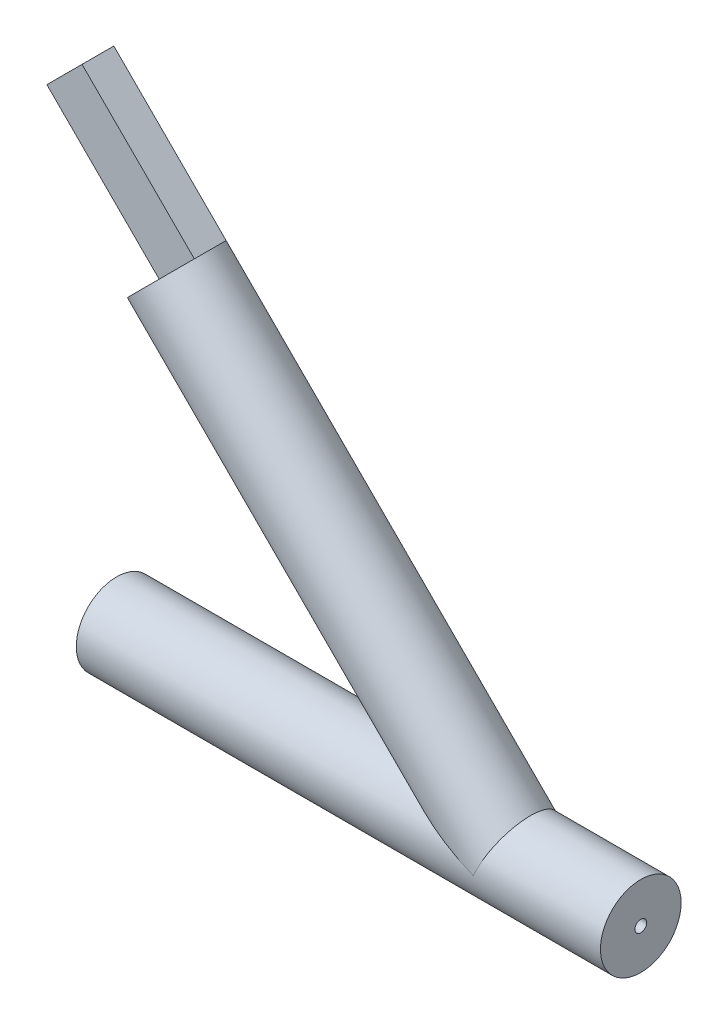
SolidWorks part; units mm, degrees
ref_plane "Front Plane" through (0, 0, 0) normal (0, 0, 1) x (1, 0, 0)
ref_plane "Top Plane" through (0, 0, 0) normal (0, 1, 0) x (1, 0, 0)
ref_plane "Right Plane" through (0, 0, 0) normal (1, 0, 0) x (0, 0, -1)
sketch "Sketch1" plane through (0, 0, 0) normal (1, 0, 0) x (0, 0, -1)
  circle A0 centre (0, 0) radius 12.7
  dimension "D1" = 25.4
extrude "Boss-Extrude1" add sketch "Sketch1" along normal blind 165 contours A0
sketch "Sketch4" plane through (0, 0, 0) normal (0, 1, 0) x (1, 0, 0)
  line L0 (125, -73.5137) -> (125, 26.4863)
  line L1 (165, -12.7) -> (165, 12.7) construction
  dimension "D1" = 40
ref_plane "Plane1" through (62.5, -62.5, 0) normal (-0.7071, 0.7071, 0) x (0.7071, 0.7071, 0)
sketch "Sketch6" plane through (0, 0, 0) normal (0, 1, 0) x (1, 0, 0)
  line L1 (165, -12.7) -> (165, 12.7) construction
  circle A0 centre (125, 0) radius 20
  dimension "D1" = 40
  dimension "D2" = 0
sketch "Sketch7" plane through (62.5, -62.5, 0) normal (-0.7071, 0.7071, 0) x (0.7071, 0.7071, 0)
  circle A0 centre (88.3883, 0) radius 12.7
  dimension "D1" = 25.4
extrude "Boss-Extrude3" add sketch "Sketch7" along normal blind 150 contours A0
sketch "Sketch10" plane through (-43.566, 43.566, 0) normal (-0.7071, 0.7071, 0) x (0, 0, 1)
  line L1 (-10, 96.2171) -> (10, 96.2171)
  line L2 (-10, 96.2171) -> (-10, 80.5596)
  line L3 (-10, 80.5596) -> (10, 80.5596)
  line L4 (10, 96.2171) -> (10, 80.5596)
  line L5 (-10, 96.2171) -> (10, 80.5596) construction
  line L6 (-10, 80.5596) -> (10, 96.2171) construction
  line L7 (-10, 96.2171) -> (0, 96.2171)
  line L8 (-10, 96.2171) -> (-10, 80.5596)
  line L9 (-10, 80.5596) -> (0, 80.5596)
  line L10 (0, 96.2171) -> (0, 80.5596)
  circle A0 centre (0, 88.3883) radius 12.7 construction
  point P0 (0, 88.3883)
  dimension "D1" = 20
extrude "Boss-Extrude8" add sketch "Sketch10" along normal blind 50 contours L10 L1 L2 L3
sketch "Sketch11" plane through (165, 0, 0) normal (1, 0, 0) x (0, 0, -1)
  circle A0 centre (0, 0) radius 1.85
  dimension "D1" = 3.7
extrude "Cut-Extrude2" cut sketch "Sketch11" against normal through all
